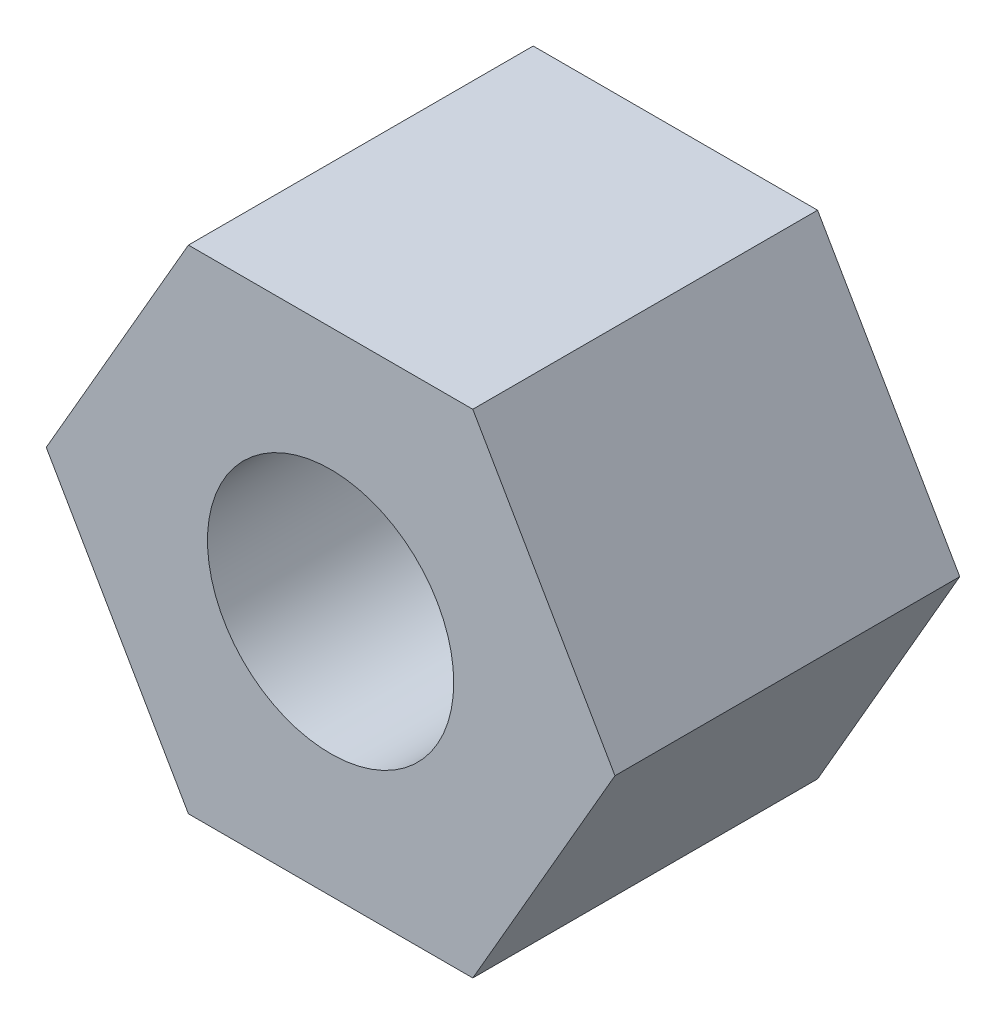
SolidWorks part; units mm, degrees
ref_plane "Front Plane" through (0, 0, 0) normal (0, 0, 1) x (1, 0, 0)
ref_plane "Top Plane" through (0, 0, 0) normal (0, 1, 0) x (1, 0, 0)
ref_plane "Right Plane" through (0, 0, 0) normal (1, 0, 0) x (0, 0, -1)
sketch "Across_flats_5" plane through (0, 0, 0) normal (0, 0, 1) x (1, 0, 0)
  line L0 (2.8868, 0) -> (1.4434, 2.5)
  line L1 (1.4434, 2.5) -> (-1.4434, 2.5)
  line L2 (-1.4434, 2.5) -> (-2.8868, 0)
  line L3 (-2.8868, 0) -> (-1.4434, -2.5)
  line L4 (-1.4434, -2.5) -> (1.4434, -2.5)
  line L5 (1.4434, -2.5) -> (2.8868, 0)
  circle A0 centre (0, 0) radius 1.25
  dimension "D1" = 2.5
extrude "Nut_thread_envelope_height_3.5" add sketch "Across_flats_5" along normal blind 3.5
